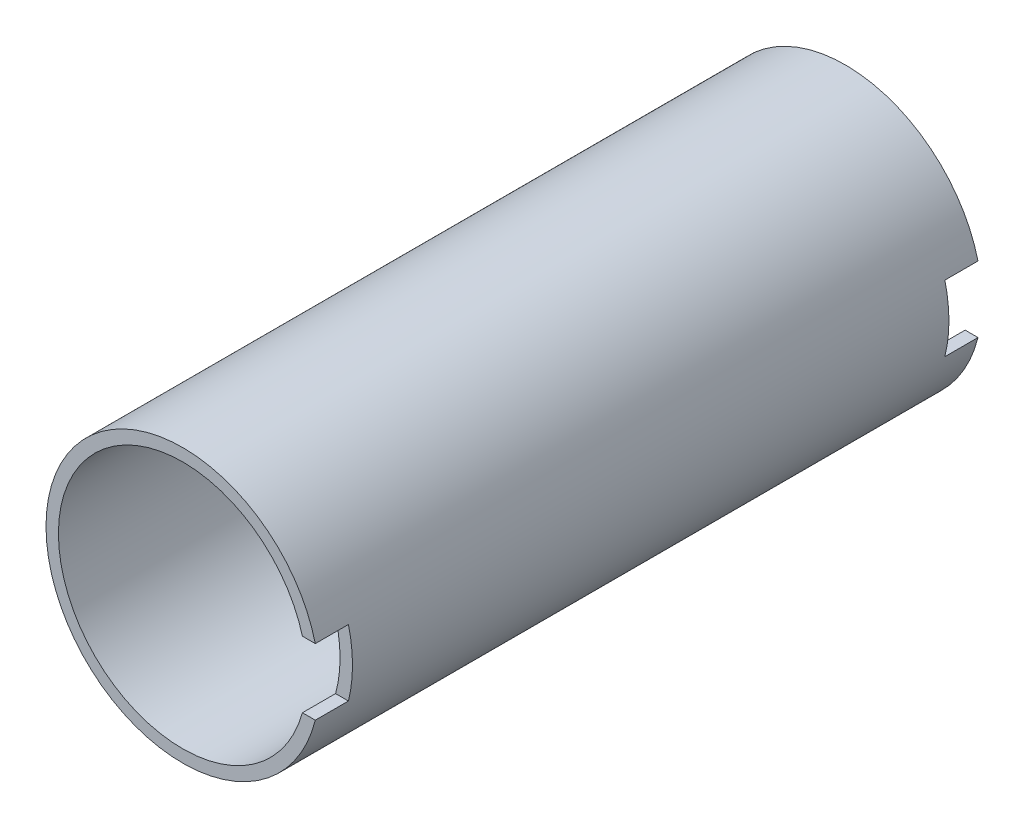
SolidWorks part; units mm, degrees
ref_plane "Front Plane" through (0, 0, 0) normal (0, 0, 1) x (1, 0, 0)
ref_plane "Top Plane" through (0, 0, 0) normal (0, 1, 0) x (1, 0, 0)
ref_plane "Right Plane" through (0, 0, 0) normal (1, 0, 0) x (0, 0, -1)
sketch "Sketch1" plane through (0, 0, 0) normal (0, 0, 1) x (1, 0, 0)
  circle A0 centre (0, 0) radius 16.5
  circle A1 centre (0, 0) radius 15
  dimension "D1" = 33
  dimension "D2" = 30
extrude "Boss-Extrude1" add sketch "Sketch1" along normal mid plane 80
sketch "Sketch3" plane through (0, 0, 0) normal (1, 0, 0) x (0, 0, -1)
  line L0 (-40, 16.5) -> (-40, -16.5) construction
  line L1 (-40, 4) -> (-36, 4)
  line L2 (-40, 4) -> (-40, -4)
  line L3 (-40, -4) -> (-36, -4)
  line L4 (-36, 4) -> (-36, -4)
  point P6 (-36, 0)
  dimension "D1" = 8
  dimension "D2" = 4
extrude "Cut-Extrude1" cut sketch "Sketch3" along normal through all
mirror "Mirror1" about plane through (0, 0, 0) normal (0, 0, 1) of "Cut-Extrude1"
